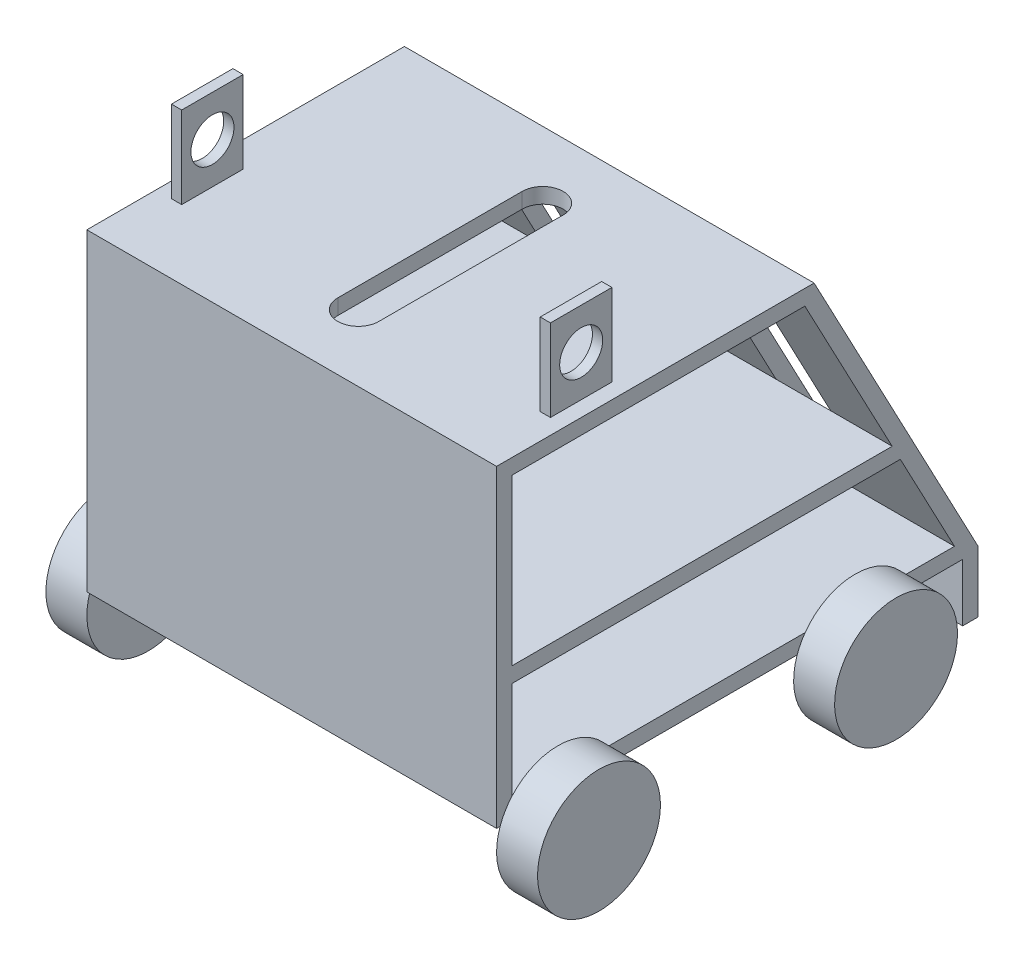
SolidWorks part; units mm, degrees
ref_plane "Front Plane" through (0, 0, 0) normal (0, 0, 1) x (1, 0, 0)
ref_plane "Top Plane" through (0, 0, 0) normal (0, 1, 0) x (1, 0, 0)
ref_plane "Right Plane" through (0, 0, 0) normal (1, 0, 0) x (0, 0, -1)
ref_plane "LeftFrame" through (63.5, 0, 0) normal (1, 0, 0) x (0, 0, -1)
sketch "Sketch2" plane through (63.5, 0, 0) normal (1, 0, 0) x (0, 0, -1)
  line L0 (-19.05, -25.4) -> (-19.05, 25.4)
  line L1 (-19.05, 25.4) -> (19.05, 25.4)
  line L2 (19.05, 25.4) -> (19.05, -25.4)
  line L3 (19.05, -25.4) -> (-19.05, -25.4)
  circle A0 centre (0, 0) radius 13.335
  point P5 (0, -25.4)
  point P8 (-19.05, 0)
  dimension "D1" = 26.67
  dimension "D2" = 50.8
  dimension "D3" = 38.1
ref_plane "RightFrame" through (292.1, 0, 0) normal (1, 0, 0) x (0, 0, -1)
ref_plane "Middle" through (177.8, 0, 0) normal (1, 0, 0) x (0, 0, -1)
sketch "Sketch4" plane through (292.1, 0, -263.652) normal (-1, 0, 0) x (0, 0, 1)
  line L0 (244.602, -25.4) -> (244.602, 25.4)
  line L1 (244.602, 25.4) -> (282.702, 25.4)
  line L2 (282.702, 25.4) -> (282.702, -25.4)
  line L3 (282.702, -25.4) -> (244.602, -25.4)
  circle A0 centre (263.652, 0) radius 13.335
  point P5 (263.652, -25.4)
  point P8 (244.602, 0)
  dimension "D1" = 26.67
  dimension "D2" = 50.8
  dimension "D3" = 38.1
extrude "Boss-Extrude2" add sketch "Sketch2" along normal mid plane 6.35
extrude "Boss-Extrude3" add sketch "Sketch4" along normal mid plane 6.35 separate body
sketch "Sketch6" plane through (177.8, 0, 0) normal (1, 0, 0) x (0, 0, -1)
  line L0 (-19.05, -25.4) -> (-61.976, -25.4)
  line L1 (-61.976, -25.4) -> (-61.976, -255.524)
  line L2 (-61.976, -255.524) -> (236.474, -255.524)
  line L3 (236.474, -255.524) -> (236.474, -217.424)
  line L4 (236.474, -217.424) -> (134.874, -25.4)
  line L5 (134.874, -25.4) -> (19.05, -25.4)
  line L6 (-61.976, 61.976) -> (61.976, 61.976) construction
  line L7 (-61.976, -61.976) -> (61.976, -61.976) construction
  line L11 (-19.05, -25.4) -> (19.05, -25.4)
  line L12 (19.05, -25.4) -> (19.05, 25.4)
  line L13 (19.05, 25.4) -> (-19.05, 25.4)
  line L14 (-19.05, 25.4) -> (-19.05, -25.4)
  line L15 (-19.05, -25.4) -> (19.05, -25.4)
  dimension "D1" = 61.976
  dimension "D2" = 196.85
  dimension "D3" = 298.45
  dimension "D5" = 61.976
  dimension "D6" = 61.976
  dimension "D7" = 61.976
  dimension "D8" = 279.4
  dimension "D10" = 317.5
  dimension "D9" = 0
extrude "Boss-Extrude4" add sketch "Sketch6" along normal mid plane 254
ref_plane "Left" through (50.8, 0, 0) normal (-1, 0, 0) x (0, 0, 1)
ref_plane "Right" through (304.8, 0, 0) normal (1, 0, 0) x (0, 0, -1)
sketch "Sketch13" plane through (177.8, 0, 0) normal (1, 0, 0) x (0, 0, -1)
  line L1 (-61.976, -255.524) -> (236.474, -255.524) construction
  line L2 (-52.451, -34.925) -> (129.1376, -34.925)
  line L3 (129.1376, -34.925) -> (226.949, -219.7886)
  line L4 (226.949, -219.7886) -> (226.949, -255.524)
  line L5 (226.949, -255.524) -> (-61.976, -255.524)
  line L7 (134.874, -25.4) -> (-61.976, -25.4) construction
  line L8 (236.474, -255.524) -> (236.474, -217.424) construction
  line L9 (236.474, -217.424) -> (134.874, -25.4) construction
  line L10 (-52.451, -34.925) -> (-52.451, -219.7886)
  line L11 (-52.451, -219.7886) -> (-61.976, -219.7886)
  line L12 (-61.976, -25.4) -> (-61.976, -255.524) construction
  line L13 (-61.976, -219.7886) -> (-61.976, -255.524)
  line L14 (226.949, -219.7886) -> (249.9218, -219.7886) construction
  dimension "D1" = 9.525
  dimension "D2" = 9.525
  dimension "D3" = 9.525
  dimension "D4" = 9.525
extrude "Cut-Extrude3" cut sketch "Sketch13" against normal mid plane 254
sketch "Sketch14" plane through (177.8, 0, 0) normal (1, 0, 0) x (0, 0, -1)
  line L0 (226.949, -219.7886) -> (-52.451, -219.7886)
  line L2 (-52.451, -219.7886) -> (-52.451, -210.2636)
  line L3 (-52.451, -210.2636) -> (221.9093, -210.2636)
  line L4 (226.949, -219.7886) -> (129.1376, -34.925) construction
  line L5 (221.9093, -210.2636) -> (226.949, -219.7886)
  line L6 (-52.451, -34.925) -> (-52.451, -219.7886) construction
  line L7 (-52.451, -146.7636) -> (188.3114, -146.7636)
  line L8 (188.3114, -146.7636) -> (183.2718, -137.2386)
  line L9 (183.2718, -137.2386) -> (-52.451, -137.2386)
  line L10 (-52.451, -137.2386) -> (-52.451, -146.7636)
  dimension "D1" = 9.525
  dimension "D2" = 63.5
  dimension "D3" = 9.525
extrude "Boss-Extrude7" add sketch "Sketch14" along normal mid plane 254
sketch "Sketch16" plane through (304.8, 0, 0) normal (1, 0, 0) x (0, 0, -1)
  line L0 (-61.976, -25.4) -> (-61.976, -219.7886) construction
  line L1 (236.474, -255.524) -> (236.474, -217.424) construction
  line L2 (-61.976, -219.7886) -> (226.949, -219.7886) construction
  circle A0 centre (-23.876, -232.4886) radius 38.1
  circle A1 centre (160.274, -232.4886) radius 38.1
  point P8 (-23.876, -245.396)
  dimension "D1" = 76.2
  dimension "D2" = 76.2
  dimension "D3" = 38.1
  dimension "D4" = 76.2
  dimension "D5" = 12.7
extrude "Boss-Extrude8" add sketch "Sketch16" along normal blind 25.4
mirror "Mirror1" about plane through (177.8, 0, 0) normal (1, 0, 0) of "Boss-Extrude8"
ref_plane "Plane8" through (0, 0, -236.474) normal (0, 0, -1) x (-1, 0, 0)
sketch "Sketch19" plane through (0, 0, -236.474) normal (0, 0, -1) x (-1, 0, 0)
  line L0 (-304.8, -217.424) -> (-304.8, -25.4) construction
  line L1 (-266.7, -63.5) -> (-232.8333, -63.5)
  line L2 (-266.7, -63.5) -> (-266.7, -179.324)
  line L3 (-266.7, -179.324) -> (-232.8333, -179.324)
  line L4 (-232.8333, -63.5) -> (-232.8333, -179.324)
  line L5 (-194.7333, -63.5) -> (-160.8667, -63.5)
  line L6 (-194.7333, -63.5) -> (-194.7333, -179.324)
  line L7 (-194.7333, -179.324) -> (-160.8667, -179.324)
  line L8 (-160.8667, -63.5) -> (-160.8667, -179.324)
  line L9 (-122.7667, -63.5) -> (-88.9, -63.5)
  line L10 (-122.7667, -63.5) -> (-122.7667, -179.324)
  line L11 (-122.7667, -179.324) -> (-88.9, -179.324)
  line L12 (-88.9, -63.5) -> (-88.9, -179.324)
  line L14 (-304.8, -25.4) -> (-50.8, -25.4) construction
  line L15 (-304.8, -217.424) -> (-50.8, -217.424) construction
  dimension "D1" = 38.1
  dimension "D2" = 33.8667
  dimension "D3" = 38.1
  dimension "D4" = 38.1
  dimension "D5" = 38.1
  dimension "D6" = 38.1
extrude "Cut-Extrude6" cut sketch "Sketch19" against normal up to surface (92.2174 mm away)
sketch "Sketch20" plane through (0, 0, 0) normal (0, 1, 0) x (1, 0, 0)
  line L0 (177.8, 93.599) -> (177.8, -20.701) construction
  line L1 (190.5, 93.599) -> (190.5, -20.701)
  line L2 (165.1, 93.599) -> (165.1, -20.701)
  line L3 (304.8, -61.976) -> (50.8, -61.976) construction
  line L4 (50.8, 134.874) -> (50.8, -61.976) construction
  arc A0 (190.5, 93.599) -> (165.1, 93.599) centre (177.8, 93.599) ccw
  arc A1 (165.1, -20.701) -> (190.5, -20.701) centre (177.8, -20.701) ccw
  point P2 (177.8, 36.449)
  point P9 (177.8, -61.976)
  point P10 (165.1, 97.7389)
  point P13 (50.8, 36.449)
  dimension "D1" = 12.7
  dimension "D2" = 114.3
extrude "Cut-Extrude7" cut sketch "Sketch20" against normal up to surface (34.925 mm away) up to face at (177.8, -34.925, -38.3433)
